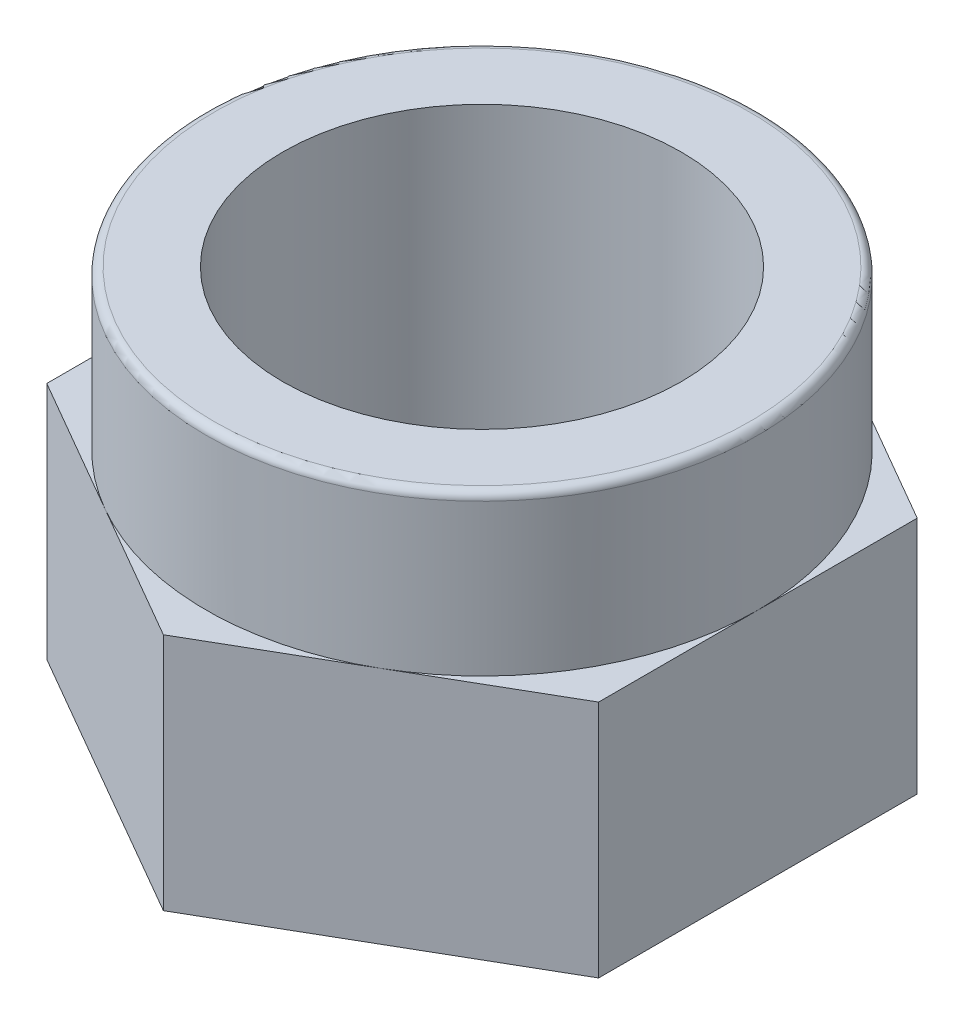
SolidWorks part; units mm, degrees
ref_plane "Front Plane" through (0, 0, 0) normal (0, 0, 1) x (1, 0, 0)
ref_plane "Top Plane" through (0, 0, 0) normal (0, 1, 0) x (1, 0, 0)
ref_plane "Right Plane" through (0, 0, 0) normal (1, 0, 0) x (0, 0, -1)
sketch "Sketch1" plane through (0, 0, 0) normal (0, 1, 0) x (1, 0, 0)
  line L1 (0, 4) -> (-3.4641, 2)
  line L2 (-3.4641, 2) -> (-3.4641, -2)
  line L3 (-3.4641, -2) -> (0, -4)
  line L4 (0, -4) -> (3.4641, -2)
  line L5 (3.4641, -2) -> (3.4641, 2)
  line L6 (3.4641, 2) -> (0, 4)
  circle A0 centre (0, 0) radius 3.4641 construction
  circle A1 centre (0, 0) radius 2.5
  dimension "D2" = 5
  dimension "D1" = 8
extrude "Boss-Extrude1" add sketch "Sketch1" along normal blind 3
sketch "Sketch2" plane through (0, 3, 0) normal (0, 1, 0) x (1, 0, 0)
  circle A0 centre (0, 0) radius 3.4641
  circle A1 centre (0, 0) radius 2.5
  dimension "D1" = 5
extrude "Boss-Extrude2" add sketch "Sketch2" along normal blind 2
fillet "Fillet1" radius 0.1 1 edges at (0, 5, 3.4641)
